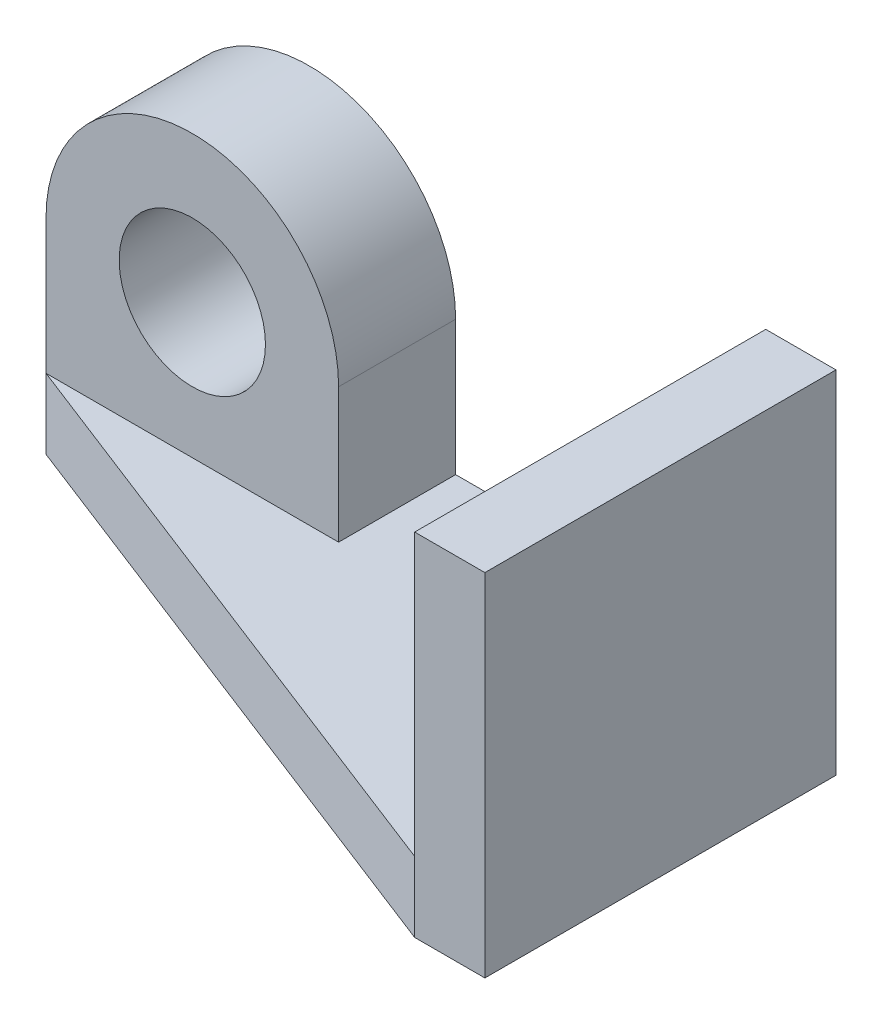
SolidWorks part; units mm, degrees
ref_plane "Front Plane" through (0, 0, 0) normal (0, 0, 1) x (1, 0, 0)
ref_plane "Top Plane" through (0, 0, 0) normal (0, 1, 0) x (1, 0, 0)
ref_plane "Right Plane" through (0, 0, 0) normal (1, 0, 0) x (0, 0, -1)
sketch "Sketch1" plane through (0, 0, 0) normal (0, 0, 1) x (1, 0, 0)
  line L0 (0, 0) -> (115, 0)
  line L1 (115, 0) -> (115, 60)
  line L2 (115, 60) -> (103, 60)
  line L3 (103, 60) -> (103, 12)
  line L4 (103, 12) -> (0, 12)
  line L5 (0, 12) -> (0, 0)
  dimension "D1" = 115
  dimension "D2" = 60
  dimension "D3" = 12
  dimension "D4" = 12
extrude "Boss-Extrude1" add sketch "Sketch1" along normal blind 60 contours L5 L0 L1 L2 L3 L4
sketch "Sketch2" plane through (0, 12, 0) normal (0, 1, 0) x (1, 0, 0)
  line L1 (0, -60) -> (0, 0) construction
  line L2 (0, -20) -> (103, -60)
  line L3 (103, -60) -> (0, -60)
  line L4 (0, -60) -> (0, -20)
extrude "Cut-Extrude1" cut sketch "Sketch2" against normal blind 12
sketch "Sketch4" plane through (0, 12, 0) normal (0, 1, 0) x (1, 0, 0)
  line L0 (0, 0) -> (0, -20)
  line L1 (0, -20) -> (50, -20)
  line L2 (50, -20) -> (50, 0)
  line L3 (103, 0) -> (0, 0) construction
  line L4 (50, 0) -> (0, 0)
  dimension "D1" = 50
extrude "Boss-Extrude3" add sketch "Sketch4" along normal blind 23
sketch "Sketch5" plane through (0, 0, 20) normal (0, 0, 1) x (1, 0, 0)
  line L0 (0, 35) -> (25, 35)
  line L1 (0, 35) -> (50, 35) construction
  line L2 (0, 35) -> (50, 35)
  arc A0 (50, 35) -> (0, 35) centre (25, 35) ccw
  dimension "D1" = 50
extrude "Boss-Extrude4" add sketch "Sketch5" against normal blind 20 contours L2 A0
sketch "Sketch6" plane through (0, 0, 20) normal (0, 0, 1) x (1, 0, 0)
  circle A0 centre (25, 35) radius 12.5
  dimension "D1" = 25
extrude "Cut-Extrude3" cut sketch "Sketch6" against normal blind 20
